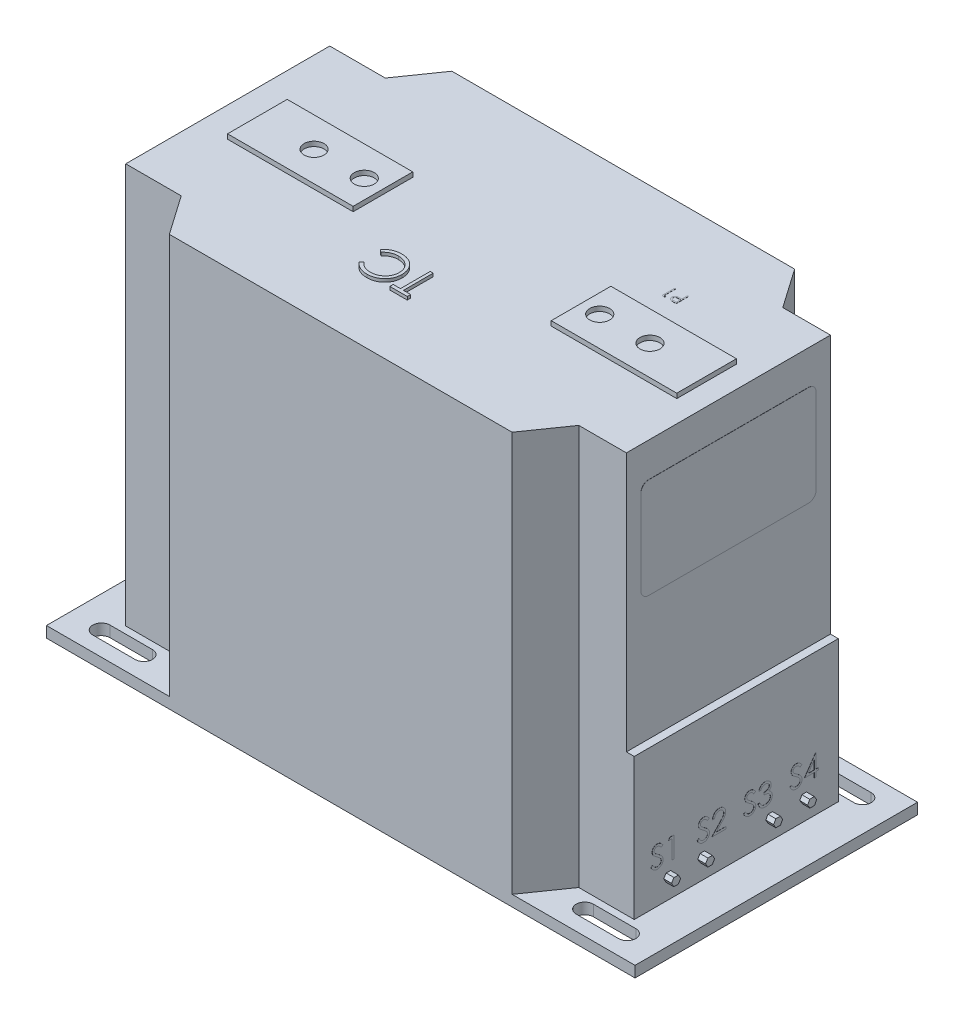
SolidWorks part; units mm, degrees
ref_plane "Alzado" through (0, 0, 0) normal (0, 0, 1) x (1, 0, 0)
ref_plane "Planta" through (0, 0, 0) normal (0, 1, 0) x (1, 0, 0)
ref_plane "Vista lateral" through (0, 0, 0) normal (1, 0, 0) x (0, 0, -1)
sketch "Croquis1" plane through (0, 0, 0) normal (0, 1, 0) x (1, 0, 0)
  line L1 (-187.5, 90) -> (187.5, 90)
  line L2 (-187.5, 90) -> (-187.5, -90)
  line L3 (-187.5, -90) -> (187.5, -90)
  line L4 (187.5, 90) -> (187.5, -90)
  line L5 (-187.5, 90) -> (187.5, -90) construction
  line L6 (-187.5, -90) -> (187.5, 90) construction
  point P0 (0, 0)
  dimension "D1" = 375
  dimension "D2" = 180
extrude "Saliente-Extruir1" add sketch "Croquis1" along normal blind 262
sketch "Croquis2" plane through (0, 262, 0) normal (0, 1, 0) x (1, 0, 0)
  line L0 (0, 0) -> (75, 0) construction
  line L1 (75, 0) -> (107, 0) construction
  line L2 (63.1078, 19) -> (63.1078, -19)
  line L3 (63.1078, -19) -> (143.1078, -19)
  line L4 (143.1078, -19) -> (143.1078, 19)
  line L5 (143.1078, 19) -> (63.1078, 19)
  line L6 (0, 0) -> (0, -29.2326) construction
  line L7 (-75, 0) -> (-107, 0) construction
  line L8 (-143.1078, 19) -> (-63.1078, 19)
  line L9 (-143.1078, -19) -> (-143.1078, 19)
  line L10 (-63.1078, -19) -> (-143.1078, -19)
  line L11 (-63.1078, 19) -> (-63.1078, -19)
  circle A0 centre (75, 0) radius 6.35
  circle A1 centre (107, 0) radius 6.35
  circle A2 centre (-107, 0) radius 6.35
  circle A3 centre (-75, 0) radius 6.35
  dimension "D2" = 12.7
  dimension "D3" = 12.7
  dimension "D1" = 75
  dimension "D4" = 32
  dimension "D5" = 38
  dimension "D6" = 80
  dimension "D7" = 19
extrude "Saliente-Extruir2" add sketch "Croquis2" along normal blind 3
sketch "Croquis3" plane through (0, 262, 0) normal (0, 1, 0) x (1, 0, 0)
  line L0 (0, 0) -> (0, 90) construction
  line L1 (187.5, 90) -> (-187.5, 90) construction
  line L2 (167.5, 75) -> (140.5, 75) construction
  line L3 (167.5, 69.5) -> (140.5, 69.5)
  line L4 (167.5, 80.5) -> (140.5, 80.5)
  line L5 (0, 0) -> (187.5, 0) construction
  line L6 (187.5, -90) -> (187.5, 90) construction
  line L7 (-167.5, 75) -> (-140.5, 75) construction
  line L8 (-167.5, 69.5) -> (-140.5, 69.5)
  line L9 (-167.5, 80.5) -> (-140.5, 80.5)
  line L10 (-167.5, -75) -> (-140.5, -75) construction
  line L11 (-167.5, -69.5) -> (-140.5, -69.5)
  line L12 (-167.5, -80.5) -> (-140.5, -80.5)
  line L13 (167.5, -75) -> (140.5, -75) construction
  line L14 (167.5, -69.5) -> (140.5, -69.5)
  line L15 (167.5, -80.5) -> (140.5, -80.5)
  line L16 (-126.6467, 65) -> (-109.1945, 90)
  line L17 (-162, 65) -> (-126.6467, 65)
  line L18 (-162, 65) -> (-162, -65)
  line L19 (-162, -65) -> (-126.6467, -65)
  line L20 (162, 65) -> (162, -65)
  line L21 (-162, 65) -> (162, -65) construction
  line L22 (-162, -65) -> (162, 65) construction
  line L23 (-126.6467, -65) -> (-109.1945, -90)
  line L24 (-187.5, -90) -> (187.5, -90) construction
  line L25 (126.6467, -65) -> (109.1945, -90)
  line L26 (126.6467, 65) -> (109.1945, 90)
  line L27 (126.6467, 65) -> (162, 65)
  line L28 (126.6467, -65) -> (162, -65)
  arc A0 (167.5, 69.5) -> (167.5, 80.5) centre (167.5, 75) ccw
  arc A1 (140.5, 80.5) -> (140.5, 69.5) centre (140.5, 75) ccw
  arc A2 (-167.5, 69.5) -> (-167.5, 80.5) centre (-167.5, 75) cw
  arc A3 (-140.5, 80.5) -> (-140.5, 69.5) centre (-140.5, 75) cw
  arc A4 (-167.5, -69.5) -> (-167.5, -80.5) centre (-167.5, -75) ccw
  arc A5 (-140.5, -80.5) -> (-140.5, -69.5) centre (-140.5, -75) ccw
  arc A6 (167.5, -69.5) -> (167.5, -80.5) centre (167.5, -75) cw
  arc A7 (140.5, -80.5) -> (140.5, -69.5) centre (140.5, -75) cw
  point P7 (154, 75)
  point P17 (-154, 75)
  point P24 (-154, -75)
  point P31 (154, -75)
  line M16 (187.5, -90) -> (187.5, 90)
  line M17 (187.5, 90) -> (-187.5, 90)
  line M18 (-187.5, 90) -> (-187.5, -90)
  line M19 (-187.5, -90) -> (187.5, -90)
  dimension "D1" = 75
  dimension "D2" = 167.5
  dimension "D3" = 27
  dimension "D4" = 11
  dimension "D5" = 162
  dimension "D6" = 130
extrude "Cortar-Extruir1" cut sketch "Croquis3" against normal blind 255 contours L23 L19 L18 L17 L16 A5 L12 A4 L11 L9 A3 L8 A2 M17 M18 M19 | L28 L25 L26 L27 L20 A1 L4 A0 L3 L15 A7 L14 A6 M19 M16 M17
sketch "Croquis4" plane through (0, 262, 0) normal (0, 1, 0) x (1, 0, 0)
  line L0 (-167.5, 75) -> (-140.5, 75) construction
  line L1 (-167.5, 80.5) -> (-140.5, 80.5)
  line L2 (-167.5, 69.5) -> (-140.5, 69.5)
  line L3 (-167.5, -75) -> (-140.5, -75) construction
  line L4 (-167.5, -69.5) -> (-140.5, -69.5)
  line L5 (-167.5, -80.5) -> (-140.5, -80.5)
  line L6 (140.5, 75) -> (167.5, 75) construction
  line L7 (140.5, 80.5) -> (167.5, 80.5)
  line L8 (140.5, 69.5) -> (167.5, 69.5)
  line L9 (140.5, -75) -> (167.5, -75) construction
  line L10 (140.5, -69.5) -> (167.5, -69.5)
  line L11 (140.5, -80.5) -> (167.5, -80.5)
  arc A0 (-167.5, 80.5) -> (-167.5, 69.5) centre (-167.5, 75) ccw
  arc A1 (-140.5, 69.5) -> (-140.5, 80.5) centre (-140.5, 75) ccw
  arc A2 (-167.5, -69.5) -> (-167.5, -80.5) centre (-167.5, -75) ccw
  arc A3 (-140.5, -80.5) -> (-140.5, -69.5) centre (-140.5, -75) ccw
  arc A4 (140.5, 80.5) -> (140.5, 69.5) centre (140.5, 75) ccw
  arc A5 (167.5, 69.5) -> (167.5, 80.5) centre (167.5, 75) ccw
  arc A6 (140.5, -69.5) -> (140.5, -80.5) centre (140.5, -75) ccw
  arc A7 (167.5, -80.5) -> (167.5, -69.5) centre (167.5, -75) ccw
  point P4 (-154, 75)
  point P13 (-154, -75)
  point P22 (154, 75)
  point P31 (154, -75)
  dimension "D1" = 11
  dimension "D2" = 11
  dimension "D3" = 11
  dimension "D4" = 11
extrude "Cortar-Extruir2" cut sketch "Croquis4" against normal blind 277
sketch "Croquis5" plane through (162, 0, 0) normal (1, 0, 0) x (0, 0, -1)
  line L0 (-65, 7) -> (-65, 97)
  line L1 (-65, 7) -> (-65, 262) construction
  line L2 (-65, 97) -> (65, 97)
  line L3 (65, 7) -> (65, 262) construction
  line L4 (65, 97) -> (65, 7)
  line L5 (65, 7) -> (-65, 7)
  line L6 (-65, 97) -> (-65, 262)
  line L7 (-65, 262) -> (65, 262)
  line L8 (65, 262) -> (65, 97)
  line M3 (65, 262) -> (-65, 262)
  line M4 (-65, 262) -> (-65, 7)
  line M6 (65, 7) -> (65, 262)
  dimension "D1" = 90
extrude "Cortar-Extruir3" cut sketch "Croquis5" against normal blind 5 contours L2 M4 M6 M3
sketch "Croquis6" plane through (162, 0, 0) normal (1, 0, 0) x (0, 0, -1)
  line L0 (0, 0) -> (0, 20) construction
  line L1 (0, 20) -> (21.6667, 20) construction
  line L3 (24.5534, 20) -> (23.11, 22.5)
  line L4 (23.11, 22.5) -> (20.2233, 22.5)
  line L5 (20.2233, 22.5) -> (18.7799, 20)
  line L6 (18.7799, 20) -> (20.2233, 17.5)
  line L7 (20.2233, 17.5) -> (23.11, 17.5)
  line L8 (23.11, 17.5) -> (24.5534, 20)
  line L9 (44.8571, 17.5461) -> (46.222, 20.0897)
  line L10 (46.222, 20.0897) -> (44.7016, 22.5437)
  line L11 (44.7016, 22.5437) -> (41.8163, 22.4539)
  line L12 (41.8163, 22.4539) -> (40.4513, 19.9103)
  line L13 (40.4513, 19.9103) -> (41.9717, 17.4563)
  line L14 (41.9717, 17.4563) -> (44.8571, 17.5461)
  line L15 (-41.9717, 17.4563) -> (-44.8571, 17.5461)
  line L16 (-40.4513, 19.9103) -> (-41.9717, 17.4563)
  line L17 (-41.8163, 22.4539) -> (-40.4513, 19.9103)
  line L18 (-44.7016, 22.5437) -> (-41.8163, 22.4539)
  line L19 (-46.222, 20.0897) -> (-44.7016, 22.5437)
  line L20 (-44.8571, 17.5461) -> (-46.222, 20.0897)
  line L21 (-23.11, 17.5) -> (-24.5534, 20)
  line L22 (-20.2233, 17.5) -> (-23.11, 17.5)
  line L23 (-18.7799, 20) -> (-20.2233, 17.5)
  line L24 (-20.2233, 22.5) -> (-18.7799, 20)
  line L25 (-23.11, 22.5) -> (-20.2233, 22.5)
  line L26 (-24.5534, 20) -> (-23.11, 22.5)
  circle A0 centre (21.6667, 20) radius 2.5 construction
  circle A1 centre (43.3367, 20) radius 2.5 construction
  circle A2 centre (-43.3367, 20) radius 2.5 construction
  circle A3 centre (-21.6667, 20) radius 2.5 construction
  dimension "D1" = 20
  dimension "D2" = 5
  dimension "D3" = 5
  dimension "D4" = 21.6667
  dimension "D5" = 21.67
extrude "Saliente-Extruir3" add sketch "Croquis6" along normal blind 5
sketch "Croquis7" plane through (162, 0, 0) normal (1, 0, 0) x (0, 0, -1)
  text T0 "\r\n\r\n\r\n  S1  S2  S3  S4" font "Century Gothic" height in points 50
extrude "Saliente-Extruir4" add sketch "Croquis7" along normal blind 0.1
sketch "Croquis8" plane through (157, 0, 0) normal (1, 0, 0) x (0, 0, -1)
  line L1 (-50.8517, 240.1495) -> (50.8517, 240.1495)
  line L2 (-55.8517, 235.1495) -> (-55.8517, 181.3189)
  line L3 (-50.8517, 176.3189) -> (50.8517, 176.3189)
  line L4 (55.8517, 235.1495) -> (55.8517, 181.3189)
  line L5 (-55.8517, 240.1495) -> (55.8517, 176.3189) construction
  line L6 (-55.8517, 176.3189) -> (55.8517, 240.1495) construction
  arc A0 (50.8517, 240.1495) -> (55.8517, 235.1495) centre (50.8517, 235.1495) cw
  arc A1 (50.8517, 176.3189) -> (55.8517, 181.3189) centre (50.8517, 181.3189) ccw
  arc A2 (-55.8517, 181.3189) -> (-50.8517, 176.3189) centre (-50.8517, 181.3189) ccw
  arc A3 (-50.8517, 240.1495) -> (-55.8517, 235.1495) centre (-50.8517, 235.1495) ccw
  point P0 (0, 208.2342)
  dimension "D1" = 5
extrude "Saliente-Extruir5" add sketch "Croquis8" along normal blind 0.1
sketch "Croquis9" plane through (-162, 0, 0) normal (-1, 0, 0) x (0, 0, 1)
  circle A0 centre (43.7616, 21.8867) radius 4.75
  dimension "D1" = 9.5
extrude "Saliente-Extruir6" add sketch "Croquis9" along normal blind 5
sketch "Croquis11" plane through (0, 262, 0) normal (0, 1, 0) x (1, 0, 0)
  line L0 (131.245, 41.1105) -> (46.938, 41.1105) construction
  line L1 (46.938, 41.1105) -> (-140.5419, 41.1105) construction
  text T0 "             P1                      " font "Century Gothic" height in points 30
extrude "Saliente-Extruir7" add sketch "Croquis11" along normal blind 0.1
sketch "Croquis12" plane through (0, 262, 0) normal (0, 1, 0) x (1, 0, 0)
  line L1 (108.9995, -29.346) -> (-107.7095, -29.346) construction
  text T0 "             TC" font "Century Gothic" height in points 80
extrude "Saliente-Extruir8" add sketch "Croquis12" along normal blind 2
ref_plane "Plano1" through (0, 0, 0) normal (0, 0, 1) x (1, 0, 0)
sketch "Croquis13" plane through (0, 265, 0) normal (0, 1, 0) x (1, 0, 0)
  line L0 (107, 6.35) -> (107, -6.35) construction
  line L1 (107, -6.35) -> (107, 0) construction
  line L2 (107, 0) -> (75, 0) construction
  line L3 (75, 0) -> (75, -6.35) construction
  circle A0 centre (107, 0) radius 6.35 construction
  circle A1 centre (107, 0) radius 6.35 construction
  circle A2 centre (75, 0) radius 6.35 construction
  circle A3 centre (75, 0) radius 6.35 construction
ref_plane "Plano2" through (107, 0, 0) normal (-1, 0, 0) x (0, 0, 1)
ref_plane "Plano3" through (91, 0, 0) normal (-1, 0, 0) x (0, 0, 1)
sketch "Croquis14" plane through (0, 265, 0) normal (0, 1, 0) x (1, 0, 0)
  line L0 (-107, -6.35) -> (-107, 6.35) construction
  line L1 (-107, 6.35) -> (-107, 0) construction
  line L2 (-107, 0) -> (-75, 0) construction
  circle A0 centre (-107, 0) radius 6.35 construction
  circle A1 centre (-107, 0) radius 6.35 construction
ref_plane "Plano4" through (-107, 0, 0) normal (1, 0, 0) x (0, 0, -1)
ref_plane "Plano5" through (-91, 0, 0) normal (1, 0, 0) x (0, 0, -1)
